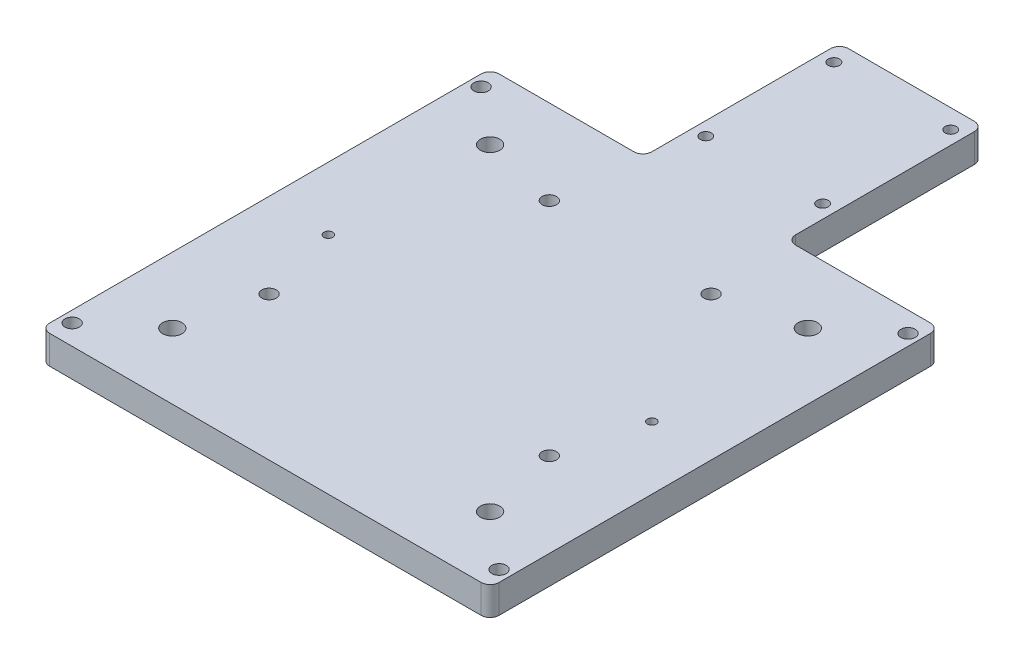
SolidWorks part; units mm, degrees
material "6061 Alloy"
ref_plane "Front Plane" through (0, 0, 0) normal (0, 0, 1) x (1, 0, 0)
ref_plane "Top Plane" through (0, 0, 0) normal (0, 1, 0) x (1, 0, 0)
ref_plane "Right Plane" through (0, 0, 0) normal (1, 0, 0) x (0, 0, -1)
sketch "Sketch1" plane through (0, 0, 0) normal (0, 1, 0) x (1, 0, 0)
  line L1 (-50, -50) -> (50, -50)
  line L2 (-50, -50) -> (-50, 50)
  line L3 (-50, 50) -> (50, 50)
  line L4 (50, -50) -> (50, 50)
  line L5 (-50, -50) -> (50, 50) construction
  line L6 (-50, 50) -> (50, -50) construction
  point P0 (0, 0)
  dimension "D1" = 100
  dimension "D2" = 100
extrude "Boss-Extrude1" add sketch "Sketch1" along normal blind 6.35
sketch "Sketch2" plane through (0, 6.35, 0) normal (0, 1, 0) x (1, 0, 0)
  line L0 (0, 0) -> (36, 0) construction
  line L1 (-47.5, -45.5) -> (47.5, -45.5) construction
  line L2 (-47.5, -45.5) -> (-47.5, 45.5) construction
  line L3 (-47.5, 45.5) -> (47.5, 45.5) construction
  line L4 (47.5, -45.5) -> (47.5, 45.5) construction
  line L5 (-47.5, -45.5) -> (47.5, 45.5) construction
  line L6 (-47.5, 45.5) -> (47.5, -45.5) construction
  line L7 (35.355, -35.355) -> (-35.355, -35.355) construction
  line L8 (35.355, -35.355) -> (35.355, 35.355) construction
  line L9 (35.355, 35.355) -> (-35.355, 35.355) construction
  line L10 (-35.355, -35.355) -> (-35.355, 35.355) construction
  line L11 (35.355, -35.355) -> (-35.355, 35.355) construction
  line L12 (35.355, 35.355) -> (-35.355, -35.355) construction
  line L13 (0, 0) -> (18, 31.1769) construction
  line L14 (0, 0) -> (31.1769, -18) construction
  line L15 (0, 0) -> (-18, 31.1769) construction
  line L16 (0, 0) -> (-36, 0) construction
  line L17 (0, 0) -> (-31.1769, -18) construction
  line L19 (-13, 61) -> (13, 61) construction
  line L20 (-13, 61) -> (-13, 89.5) construction
  line L21 (-13, 89.5) -> (13, 89.5) construction
  line L22 (13, 61) -> (13, 89.5) construction
  line L23 (-13, 61) -> (13, 89.5) construction
  line L24 (-13, 89.5) -> (13, 61) construction
  circle A0 centre (0, 0) radius 36 construction
  point P0 (0, 0)
  point P6 (0, 0)
  point P21 (0, 75.25)
  dimension "D4" = 72
  dimension "D1" = 91
  dimension "D2" = 95
  dimension "D3" = 70.71
  dimension "D5" = 60
  dimension "D6" = 30
  dimension "D7" = 60
  dimension "D8" = 30
  dimension "D9" = 26
  dimension "D11" = 28.5
  dimension "D12" = 75.25
sketch "Sketch10" plane through (0, 6.35, 0) normal (0, 1, 0) x (1, 0, 0)
  line L0 (-16, 50) -> (-16, 93.75)
  line L1 (50, 50) -> (-50, 50) construction
  line L2 (-16, 93.75) -> (16, 93.75)
  line L3 (16, 93.75) -> (16, 50)
  line L4 (-13, 61) -> (13, 89.5) construction
  line L5 (16, 56.75) -> (-16, 56.75) construction
  line L6 (16, 56.75) -> (16, 93.75) construction
  line L7 (16, 93.75) -> (-16, 93.75) construction
  line L8 (-16, 56.75) -> (-16, 93.75) construction
  line L9 (16, 56.75) -> (-16, 93.75) construction
  line L10 (16, 93.75) -> (-16, 56.75) construction
  line L11 (-16, 50) -> (16, 50)
  point P4 (0, 93.75)
  point P7 (0, 75.25)
  dimension "D1" = 37
  dimension "D2" = 32
extrude "Boss-Extrude2" add sketch "Sketch10" against normal up to surface (6.35 mm away) up to face at (0, 0, 0)
sketch "Sketch12" plane through (0, 6.35, 0) normal (0, 1, 0) x (1, 0, 0)
  line L0 (0, -26) -> (0, 26) construction
  line L1 (-9, -26) -> (-9, 26)
  line L2 (9, -26) -> (9, 26)
  line L3 (-20, 0) -> (20, 0) construction
  line L4 (-20, 9) -> (20, 9)
  line L5 (-20, -9) -> (20, -9)
  arc A0 (-9, -26) -> (9, -26) centre (0, -26) ccw
  arc A1 (9, 26) -> (-9, 26) centre (0, 26) ccw
  arc A2 (-20, 9) -> (-20, -9) centre (-20, 0) ccw
  arc A3 (20, -9) -> (20, 9) centre (20, 0) ccw
  circle A4 centre (0, 0) radius 20
  point P2 (0, 0)
  point P9 (0, 0)
  dimension "D2" = 9
  dimension "D3" = 40
  dimension "D1" = 52
  dimension "D4" = 40
extrude "Cut-Extrude2" [suppressed] cut sketch "Sketch12" against normal through all contours L1 L5 L2 L4 | L2 A1 L1 L4 | L5 A3 L4 L2 | L1 A0 L2 L5 | A4
sketch "Sketch3" plane through (0, 6.35, 0) normal (0, 1, 0) x (1, 0, 0)
  circle A0 centre (-36, 0) radius 0.9919
  circle A1 centre (36, 0) radius 0.9919
  dimension "D1" = 1.9837
extrude "Cut-Extrude1" cut sketch "Sketch3" against normal through all
hole_wizard "M3 Clearance Hole1" positions "Sketch4" profile "Sketch5" hole size "M3" standard "ANSI Metric" end condition through all
sketch "Sketch4" plane through (0, 6.35, 0) normal (0, 1, 0) x (1, 0, 0)
  line L0 (0, 0) -> (18, 31.1769) construction
  point P0 (-47.5, 45.5)
  point P3 (47.5, 45.5)
  point P6 (47.5, -45.5)
  point P9 (-47.5, -45.5)
  point P12 (-31.1769, -18)
  point P15 (31.1769, -18)
  point P18 (18, 31.1769)
  point P22 (-18, 31.1769)
sketch "Sketch5" plane through (-47.5, 6.35, -45.5) normal (1, 0, 0) x (0, 0, 1)
  line L0 (0, 0) -> (0, 6.35)
  line L1 (0, 6.35) -> (1.6, 6.35)
  line L2 (1.6, 6.35) -> (1.6, 0)
  line L5 (1.6, 0) -> (0, 0)
  line L11 (0, -6.35) -> (0, 107.95) construction
  dimension "Thru Hole Dia." = 3.2
  dimension "Thru Hole Depth" = 6.35
hole_wizard "M4 Clearance Hole1" positions "Sketch6" profile "Sketch7" hole size "M4" standard "ANSI Metric" end condition through all
sketch "Sketch6" plane through (0, 6.35, 0) normal (0, 1, 0) x (1, 0, 0)
  point P0 (-35.355, -35.355)
  point P3 (-35.355, 35.355)
  point P6 (35.355, 35.355)
  point P9 (35.355, -35.355)
sketch "Sketch7" plane through (-35.355, 6.35, 35.355) normal (1, 0, 0) x (0, 0, 1)
  line L0 (0, 0) -> (0, 6.35)
  line L1 (0, 6.35) -> (2.15, 6.35)
  line L2 (2.15, 6.35) -> (2.15, 0)
  line L5 (2.15, 0) -> (0, 0)
  line L11 (0, -6.35) -> (0, 107.95) construction
  dimension "Thru Hole Dia." = 4.3
  dimension "Thru Hole Depth" = 6.35
hole_wizard "M3x0.5 Tapped Hole1" positions "Sketch8" profile "Sketch9" tap size "M3x0.5" standard "ANSI Metric" end condition through all
sketch "Sketch8" plane through (0, 6.35, 0) normal (0, 1, 0) x (1, 0, 0)
  point P0 (-13, 89.5)
  point P3 (13, 89.5)
  point P6 (13, 61)
  point P9 (-13, 61)
sketch "Sketch9" plane through (-13, 6.35, -89.5) normal (1, 0, 0) x (0, 0, 1)
  line L0 (0, 0) -> (0, 6.35)
  line L1 (0, 6.35) -> (1.25, 6.35)
  line L2 (1.25, 6.35) -> (1.25, 0)
  line L5 (1.25, 0) -> (0, 0)
  line L11 (0, -6.35) -> (0, 107.95) construction
  dimension "Thru Tap Drill Dia." = 2.5
  dimension "Thru Tap Drill Depth" = 6.35
fillet "Fillet1" radius 2 8 edges at (50, 3.175, 50) (-50, 3.175, 50) (-16, 3.175, -50) (-16, 3.175, -93.75) (16, 3.175, -93.75) (16, 3.175, -50) (50, 3.175, -50) (-50, 3.175, -50)
